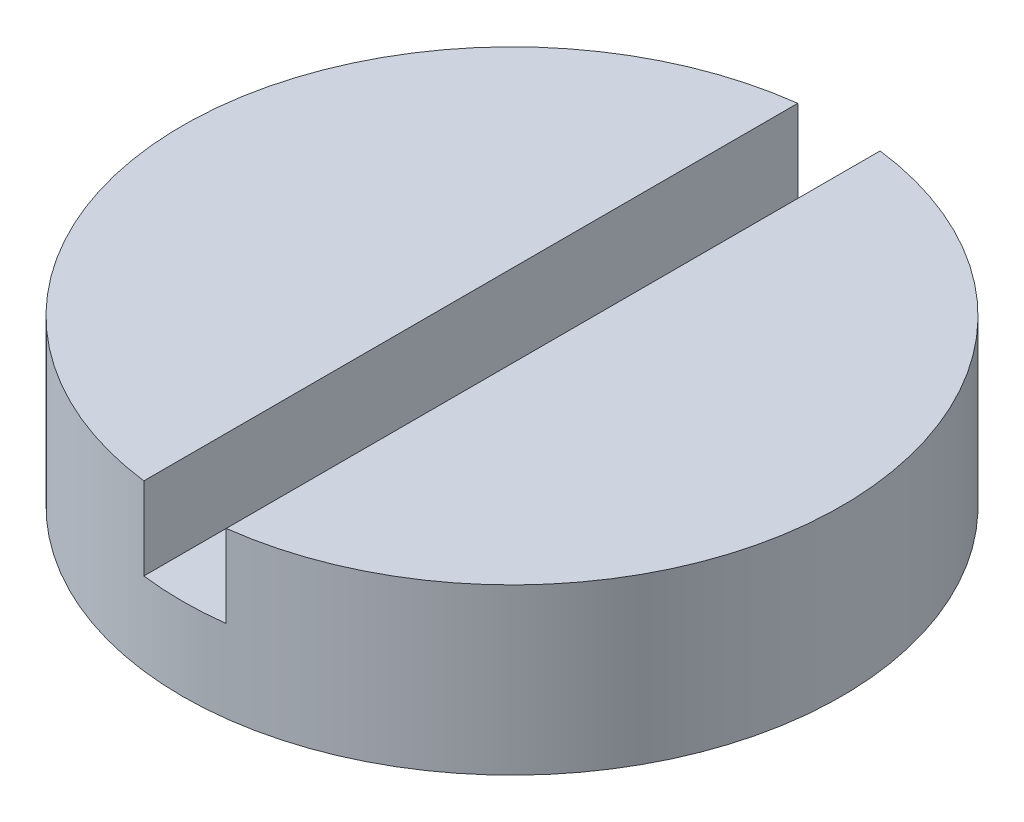
SolidWorks part; units mm, degrees
ref_plane "Alzado" through (0, 0, 0) normal (0, 0, 1) x (1, 0, 0)
ref_plane "Planta" through (0, 0, 0) normal (0, 1, 0) x (1, 0, 0)
ref_plane "Vista lateral" through (0, 0, 0) normal (1, 0, 0) x (0, 0, -1)
sketch "Croquis1" plane through (0, 0, 0) normal (0, 1, 0) x (1, 0, 0)
  circle A0 centre (0, 0) radius 4
  dimension "D1" = 8
extrude "Saliente-Extruir1" add sketch "Croquis1" along normal blind 2
sketch "Croquis2" plane through (0, 2, 0) normal (0, 1, 0) x (1, 0, 0)
  line L0 (-0.5, 3.9686) -> (-0.5, -3.9686)
  line L1 (0, 4) -> (0, -4) construction
  line L2 (0.5, 3.9686) -> (0.5, -3.9686)
  circle A0 centre (0, 0) radius 4 construction
  arc A1 (-0.5, -3.9686) -> (0.5, -3.9686) centre (0, 0) ccw
  arc A2 (0.5, 3.9686) -> (-0.5, 3.9686) centre (0, 0) ccw
  dimension "D1" = 0.5
  dimension "D2" = 0.5
extrude "Cortar-Extruir1" cut sketch "Croquis2" against normal blind 1
